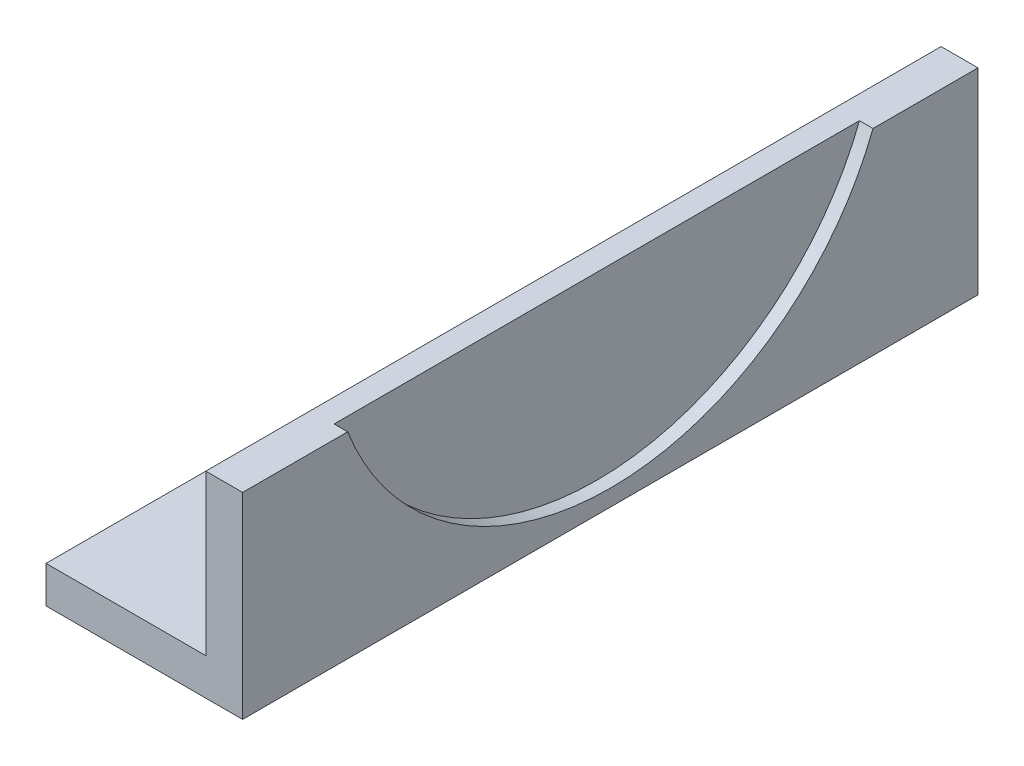
SolidWorks part; units mm, degrees
ref_plane "Front" through (0, 0, 0) normal (0, 0, 1) x (1, 0, 0)
ref_plane "Top" through (0, 0, 0) normal (0, 1, 0) x (1, 0, 0)
ref_plane "Right" through (0, 0, 0) normal (1, 0, 0) x (0, 0, -1)
sketch "Sketch1" plane through (0, 0, 0) normal (0, 0, 1) x (1, 0, 0)
  line L0 (15.875, 15.875) -> (25.4, 25.4) construction
  line L1 (-25.4, -25.4) -> (25.4, -25.4)
  line L2 (-25.4, -25.4) -> (-25.4, -15.875)
  line L3 (15.875, 25.4) -> (25.4, 25.4)
  line L4 (25.4, -25.4) -> (25.4, 25.4)
  line L5 (-25.4, -25.4) -> (-15.875, -15.875) construction
  line L9 (-25.4, -15.875) -> (15.875, -15.875)
  line L10 (15.875, 25.4) -> (15.875, -15.875)
  line L13 (15.875, -15.875) -> (25.4, -25.4) construction
  point P0 (0, 0)
  point P9 (-4.7625, 4.7625)
  dimension "D1" = 50.8
  dimension "D3" = 9.525
extrude "Boss-Extrude1" add sketch "Sketch1" along normal blind 190
sketch "Sketch3" plane through (25.4, 0, 0) normal (1, 0, 0) x (0, 0, -1)
  circle A2 centre (-95, 51.6) radius 72.75
  dimension "D1" = 145.5
extrude "Cut-Extrude3" cut sketch "Sketch3" against normal blind 3.5
